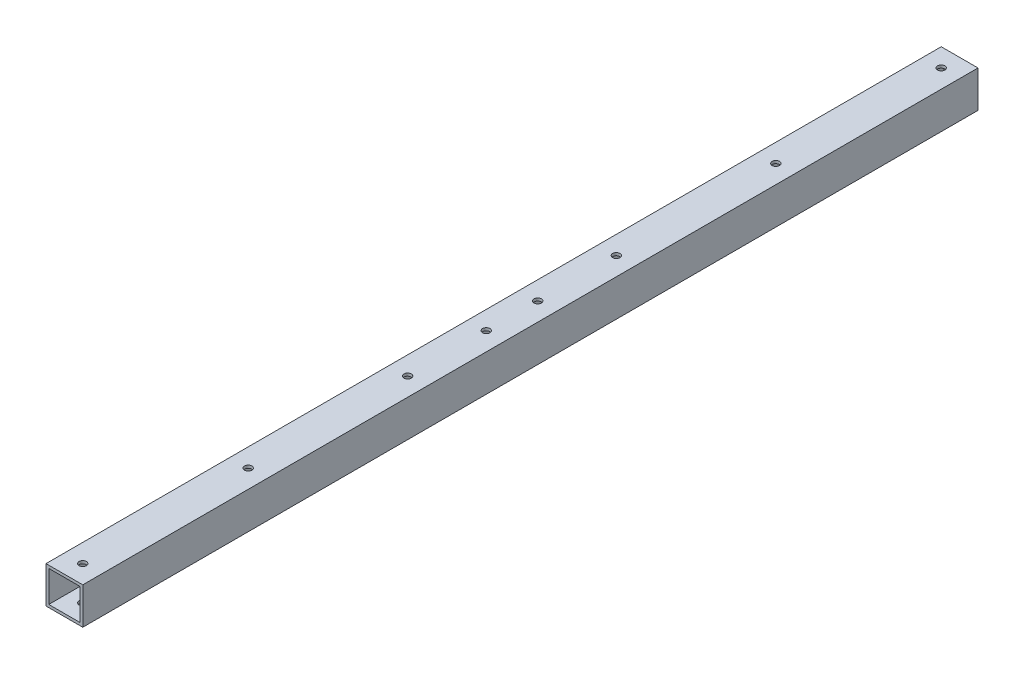
SolidWorks part; units mm, degrees
material "6061 合金"
ref_plane "前视基准面" through (0, 0, 0) normal (0, 0, 1) x (1, 0, 0)
ref_plane "上视基准面" through (0, 0, 0) normal (0, 1, 0) x (1, 0, 0)
ref_plane "右视基准面" through (0, 0, 0) normal (1, 0, 0) x (0, 0, -1)
sketch "草图1" plane through (0, 0, 0) normal (0, 0, 1) x (1, 0, 0)
  line L1 (-10, 10) -> (10, 10)
  line L2 (-10, 10) -> (-10, -10)
  line L3 (-10, -10) -> (10, -10)
  line L4 (10, 10) -> (10, -10)
  line L5 (-10, 10) -> (10, -10) construction
  line L6 (-10, -10) -> (10, 10) construction
  line L7 (-8.5, 8.5) -> (8.5, 8.5)
  line L8 (-8.5, 8.5) -> (-8.5, -8.5)
  line L9 (-8.5, -8.5) -> (8.5, -8.5)
  line L10 (8.5, 8.5) -> (8.5, -8.5)
  line L11 (-8.5, 8.5) -> (8.5, -8.5) construction
  line L12 (-8.5, -8.5) -> (8.5, 8.5) construction
  point P0 (0, 0)
  point P5 (0, 0)
  dimension "D1" = 20
  dimension "D2" = 20
  dimension "D3" = 17
  dimension "D4" = 17
extrude "凸台-拉伸1" add sketch "草图1" along normal blind 487
sketch "草图3" plane through (0, 10, 0) normal (0, 1, 0) x (1, 0, 0)
  line L0 (0, -11) -> (0, 11) construction
  line L1 (-11, 0) -> (11, 0) construction
  line L2 (10, -487) -> (-10, -487) construction
  circle A0 centre (0, -10) radius 2
  circle A1 centre (0, -477) radius 2
  circle A2 centre (0, -100) radius 2
  circle A3 centre (0, -387) radius 2
  circle A4 centre (0, -186.75) radius 2
  circle A5 centre (0, -300.25) radius 2
  dimension "D1" = 10
  dimension "D2" = 10
  dimension "D3" = 90
  dimension "D4" = 90
  dimension "D5" = 186.75
  dimension "D6" = 186.75
extrude "切除-拉伸2" cut sketch "草图3" against normal blind 20
sketch "草图4" plane through (0, 10, 0) normal (0, 1, 0) x (1, 0, 0)
  line L0 (0, -11) -> (0, 11) construction
  line L2 (10, -487) -> (-10, -487) construction
  circle A0 centre (0, -229.5) radius 2
  circle A1 centre (0, -257.5) radius 2
  point P10 (96.1109, -56.4134)
  dimension "D1" = 229.5
  dimension "D2" = 28
extrude "切除-拉伸3" cut sketch "草图4" against normal blind 20
